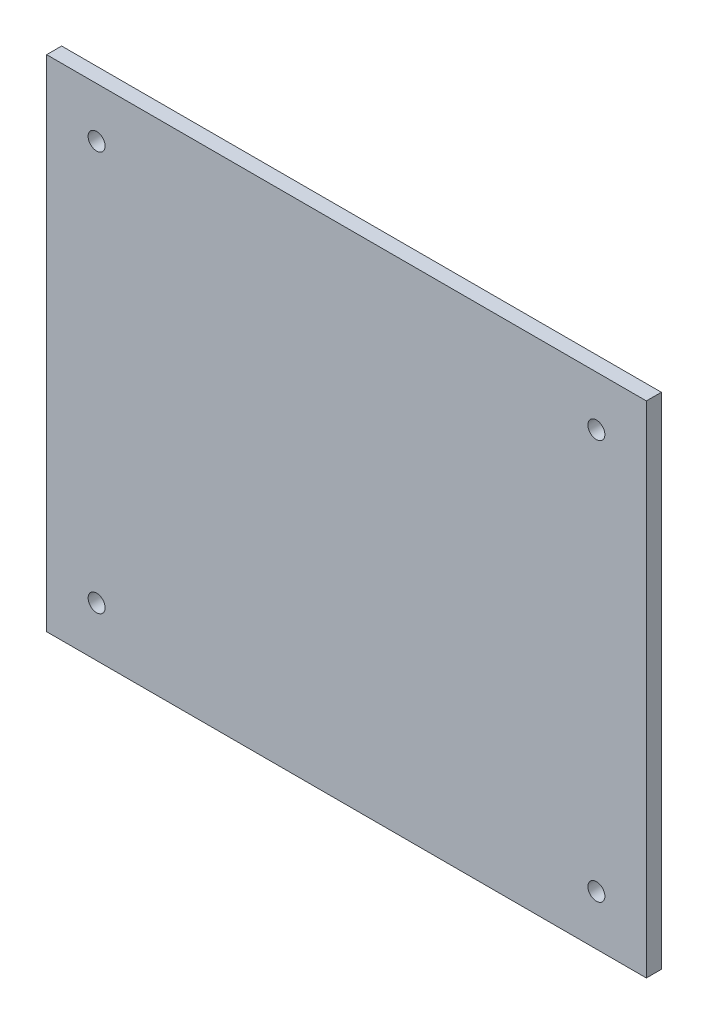
SolidWorks part; units mm, degrees
ref_plane "前视基准面" through (0, 0, 0) normal (0, 0, 1) x (1, 0, 0)
ref_plane "上视基准面" through (0, 0, 0) normal (0, 1, 0) x (1, 0, 0)
ref_plane "右视基准面" through (0, 0, 0) normal (1, 0, 0) x (0, 0, -1)
other "Configuration Table"
sketch "外形与孔位_camera_removable_panel" plane through (0, 0, 0) normal (0, 0, 1) x (1, 0, 0)
  line L0 (0, 0) -> (120, 0)
  line L1 (120, 0) -> (120, 100)
  line L2 (120, 100) -> (0, 100)
  line L3 (0, 100) -> (0, 0)
  circle A0 centre (10, 10) radius 1.7
  circle A1 centre (10, 90) radius 1.7
  circle A2 centre (110, 10) radius 1.7
  circle A3 centre (110, 90) radius 1.7
extrude "板厚_3mm" add sketch "外形与孔位_camera_removable_panel" along normal blind 3
